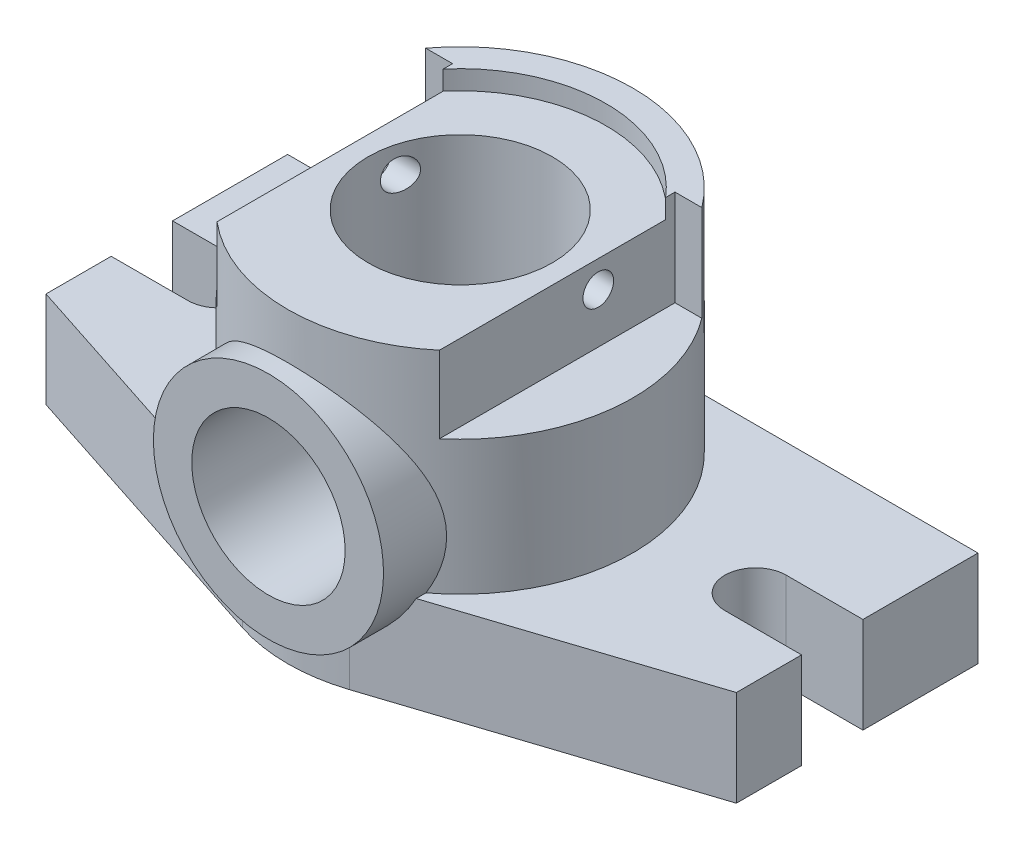
SolidWorks part; units mm, degrees
ref_plane "前视基准面" through (0, 0, 0) normal (0, 0, 1) x (1, 0, 0)
ref_plane "上视基准面" through (0, 0, 0) normal (0, 1, 0) x (1, 0, 0)
ref_plane "右视基准面" through (0, 0, 0) normal (1, 0, 0) x (0, 0, -1)
sketch "草图1" plane through (0, 0, 0) normal (0, 1, 0) x (1, 0, 0)
  line L0 (0, 88.3534) -> (0, -88.3534) construction
  line L1 (-90, 38) -> (90, 38)
  line L2 (90, 38) -> (90, 8)
  line L3 (90, -25) -> (13.9429, -49.7855)
  line L4 (-90, 38) -> (-90, 8)
  line L5 (-90, -25) -> (-13.9429, -49.7855)
  line L6 (-236.3954, 0) -> (142.3943, 0) construction
  line L7 (-90, 8) -> (-70, 8)
  line L8 (-90, -8) -> (-70, -8)
  line L9 (-90, -8) -> (-90, -25)
  line L10 (90, -8) -> (70, -8)
  line L11 (90, 8) -> (70, 8)
  line L12 (90, -8) -> (90, -25)
  arc A0 (-13.9429, -49.7855) -> (13.9429, -49.7855) centre (0, -7) ccw
  arc A1 (-70, -8) -> (-70, 8) centre (-70, 0) ccw
  arc A2 (70, -8) -> (70, 8) centre (70, 0) cw
  point P15 (-67.4902, 0)
  point P16 (0, 0)
  dimension "D4" = 90
  dimension "D1" = 63
  dimension "D2" = 180
  dimension "D3" = 38
  dimension "D5" = 16
  dimension "D6" = 20
extrude "凸台-拉伸1" add sketch "草图1" along normal blind 25
sketch "草图2" plane through (0, 25, 0) normal (0, 1, 0) x (1, 0, 0)
  circle A0 centre (0, -7) radius 45
  arc A1 (-13.9429, -49.7855) -> (13.9429, -49.7855) centre (0, -7) ccw construction
extrude "凸台-拉伸2" add sketch "草图2" along normal blind 60
sketch "草图3" plane through (0, 85, 0) normal (0, 1, 0) x (1, 0, 0)
  circle A0 centre (0, -7) radius 38
  circle A1 centre (0, -7) radius 45 construction
  dimension "D1" = 76
extrude "切除-拉伸1" cut sketch "草图3" against normal blind 5
sketch "草图4" plane through (0, 80, 0) normal (0, 1, 0) x (1, 0, 0)
  circle A0 centre (0, -7) radius 24
  circle A1 centre (0, -7) radius 38 construction
  dimension "D1" = 48
extrude "切除-拉伸2" cut sketch "草图4" against normal through all
ref_plane "基准面4" through (0, 60, 0) normal (0, 1, 0) x (1, 0, 0)
sketch "草图5" plane through (0, 60, 0) normal (0, 1, 0) x (1, 0, 0)
  line L0 (0, 41.8731) -> (0, -58.6073) construction
  line L1 (-29, 20) -> (-29, -41.4093)
  line L2 (-29, 20) -> (-36, 20)
  line L3 (29, 20) -> (29, -41.4093)
  line L4 (29, 20) -> (36, 20)
  arc A0 (-36, 20) -> (-29, -41.4093) centre (0, -7) ccw
  circle A1 centre (0, -7) radius 45 construction
  arc A2 (29, -41.4093) -> (36, 20) centre (0, -7) ccw
  point P4 (29, 20)
  point P6 (29, -41.4093)
  point P8 (0, 0)
  point P9 (-4.3187, -7.5469)
  point P13 (0, 0)
  point P14 (0, 0)
  dimension "D1" = 58
  dimension "D2" = 20
extrude "切除-拉伸3" cut sketch "草图5" along normal through all
sketch "草图7" plane through (0, 80, 0) normal (0, 1, 0) x (1, 0, 0)
  line L1 (-47.6092, 0) -> (48.8287, 0)
  line L2 (-47.6092, 0) -> (-47.6092, -64.7878)
  line L3 (-47.6092, -64.7878) -> (48.8287, -64.7878)
  line L4 (48.8287, 0) -> (48.8287, -64.7878)
extrude "切除-拉伸4" cut sketch "草图7" along normal through all
sketch "草图8" plane through (-29, 0, 0) normal (-1, 0, 0) x (0, 0, 1)
  line L0 (-17.5561, 80) -> (41.4093, 80) construction
  line L1 (-20, 85) -> (-20, 60) construction
  circle A0 centre (0, 73) radius 4
  point P4 (0, 0)
  point P5 (0, 0)
  dimension "D2" = 8
  dimension "D1" = 7
  dimension "D3" = 20
extrude "切除-拉伸5" cut sketch "草图8" against normal through all
ref_plane "基准面5" through (0, 0, 57) normal (0, 0, -1) x (-1, 0, 0)
sketch "草图9" plane through (0, 0, 57) normal (0, 0, -1) x (-1, 0, 0)
  line L0 (-13.9429, 0) -> (-90, 0) construction
  circle A0 centre (0, 38) radius 30
  point P5 (0, 0)
  dimension "D1" = 60
  dimension "D3" = 38
extrude "凸台-拉伸3" add sketch "草图9" along normal up to next
sketch "草图10" plane through (0, 0, 57) normal (0, 0, 1) x (1, 0, 0)
  circle A0 centre (0, 38) radius 20
  circle A3 centre (0, 38) radius 30 construction
  dimension "D1" = 40
extrude "切除-拉伸6" cut sketch "草图10" against normal up to surface (36.7335 mm away)
